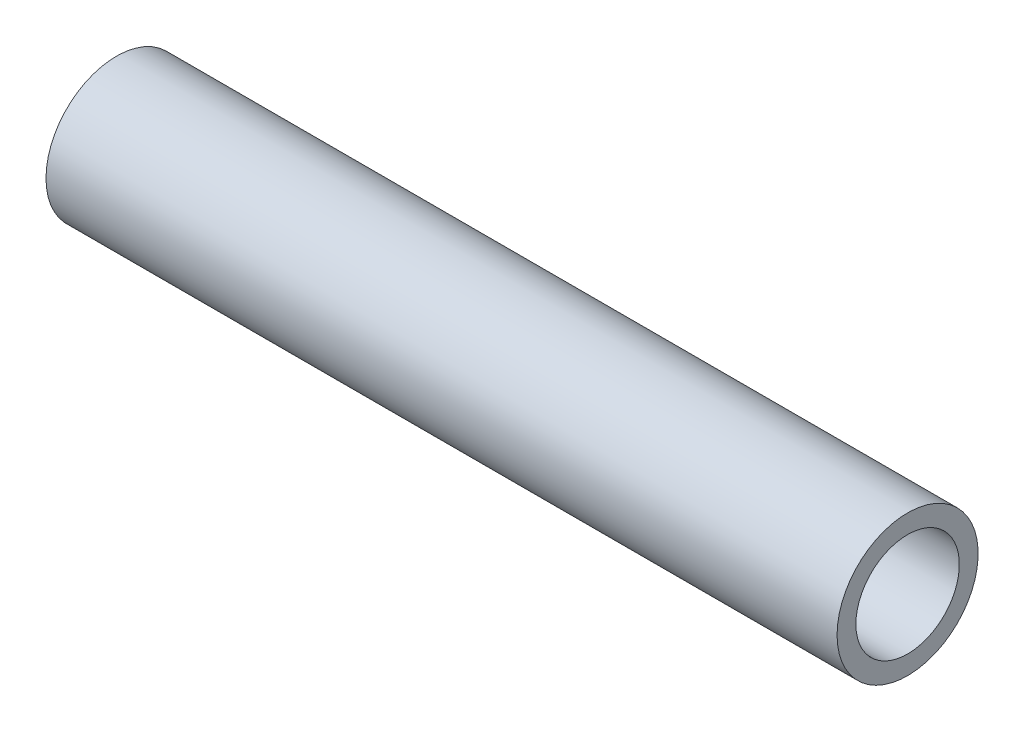
SolidWorks part; units mm, degrees
ref_plane "Front Plane" through (0, 0, 0) normal (0, 0, 1) x (1, 0, 0)
ref_plane "Top Plane" through (0, 0, 0) normal (0, 1, 0) x (1, 0, 0)
ref_plane "Right Plane" through (0, 0, 0) normal (1, 0, 0) x (0, 0, -1)
sketch "Axial profile (mm)" plane through (0, 0, 0) normal (0, 0, 1) x (1, 0, 0)
  line L0 (-110, 0) -> (75, 0) construction
  line L1 (0, 1.65) -> (25.2357, 1.65)
  line L2 (25.2357, 1.65) -> (25.2357, 2.25)
  line L3 (25.2357, 2.25) -> (0, 2.25)
  line L4 (0, 2.25) -> (0, 1.65)
revolve "Full revolution" add sketch "Axial profile (mm)" angle 360 about L0
